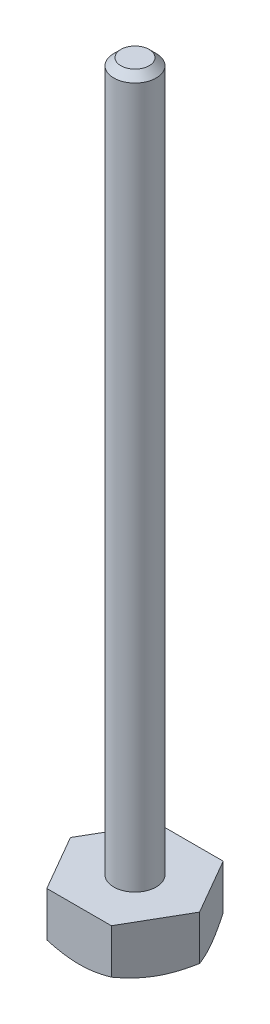
SolidWorks part; units mm, degrees
ref_plane "Front Plane" through (0, 0, 0) normal (0, 0, 1) x (1, 0, 0)
ref_plane "Top Plane" through (0, 0, 0) normal (0, 1, 0) x (1, 0, 0)
ref_plane "Right Plane" through (0, 0, 0) normal (1, 0, 0) x (0, 0, -1)
sketch "Sketch1" plane through (0, 0, 0) normal (0, 1, 0) x (1, 0, 0)
  line L1 (4.5611, 0) -> (2.2805, 3.95)
  line L2 (2.2805, 3.95) -> (-2.2805, 3.95)
  line L3 (-2.2805, 3.95) -> (-4.5611, 0)
  line L4 (-4.5611, 0) -> (-2.2805, -3.95)
  line L5 (-2.2805, -3.95) -> (2.2805, -3.95)
  line L6 (2.2805, -3.95) -> (4.5611, 0)
  circle A0 centre (0, 0) radius 3.95 construction
  dimension "D1" = 7.9
extrude "Boss-Extrude1" add sketch "Sketch1" along normal blind 53.5
sketch "Sketch2" plane through (0, 53.5, 0) normal (0, 1, 0) x (1, 0, 0)
  circle A0 centre (0, 0) radius 1.5
  dimension "D1" = 3
extrude "Cut-Extrude1" cut sketch "Sketch2" against normal blind 50 flip side to cut
sketch "Sketch3" plane through (0, 0, 0) normal (1, 0, 0) x (0, 0, -1)
  line L0 (3.95, 0) -> (5.249, 0.75)
  line L1 (5.249, 0.75) -> (5.249, -0.75)
  line L2 (5.249, -0.75) -> (3.95, 0)
  dimension "D1" = 1.5
ref_axis "Axis1" through (0, 3.5, 0) along (0, 1, 0)
revolve "Cut-Revolve1" cut sketch "Sketch3" angle 360 about axis through (0, 3.5, 0) along (0, 1, 0)
chamfer "Chamfer1" distance 0.5 angle 45 1 edges at (0, 53.5, 1.5)
sketch "Sketch5" plane through (0, 53.5, 0) normal (0, 1, 0) x (1, 0, 0)
  circle A0 centre (0, 0) radius 3
  dimension "D1" = 6
curve "Helix/Spiral1" pitch 0.7 height 46 turns 65.7143
ref_plane "Plane1" through (0, 53.5, 3) normal (-0.9993, -0.0371, 0) x (0, 0, 1)
